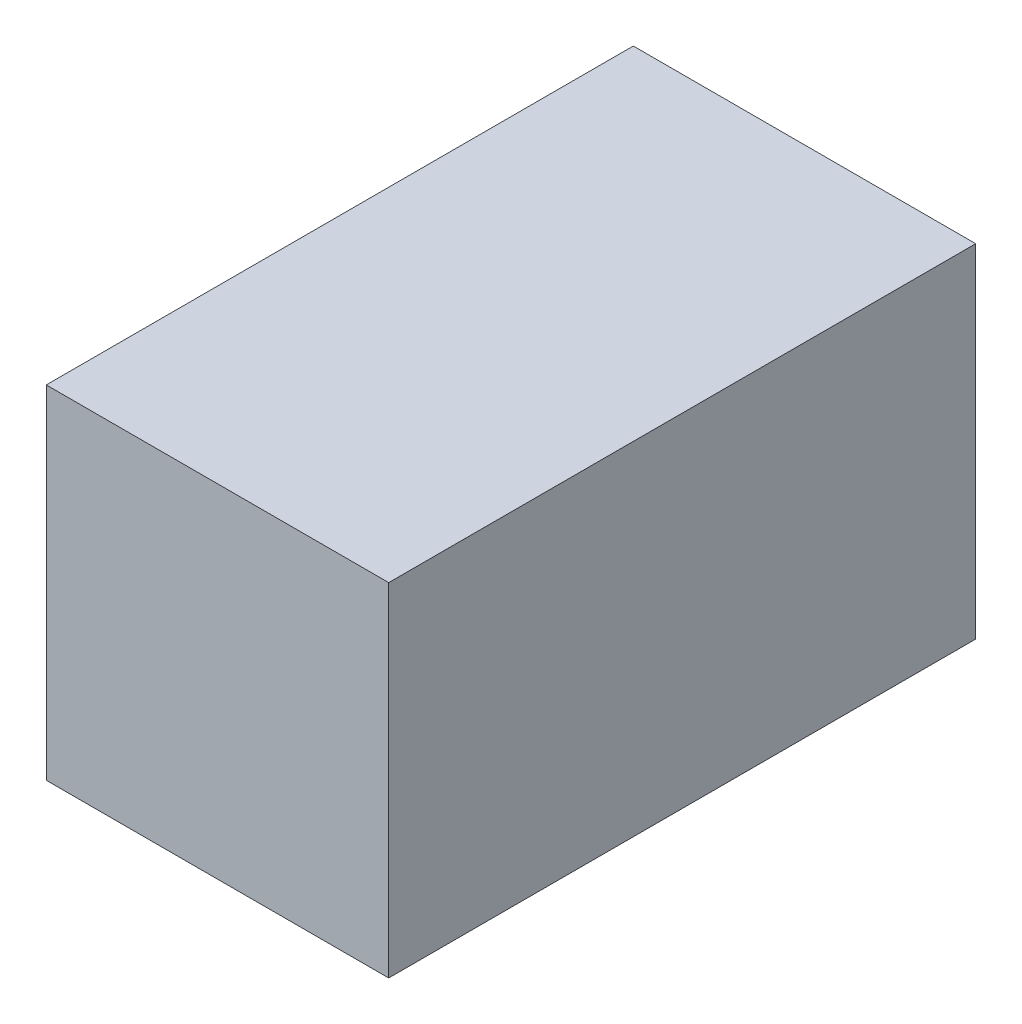
SolidWorks part; units mm, degrees
ref_plane "Front Plane" through (0, 0, 0) normal (0, 0, 1) x (1, 0, 0)
ref_plane "Top Plane" through (0, 0, 0) normal (0, 1, 0) x (1, 0, 0)
ref_plane "Right Plane" through (0, 0, 0) normal (1, 0, 0) x (0, 0, -1)
sketch "Sketch1" plane through (0, 0, 0) normal (0, 0, 1) x (1, 0, 0)
  line L1 (88.9, -88.9) -> (-88.9, -88.9)
  line L2 (88.9, -88.9) -> (88.9, 88.9)
  line L3 (88.9, 88.9) -> (-88.9, 88.9)
  line L4 (-88.9, -88.9) -> (-88.9, 88.9)
  line L5 (88.9, -88.9) -> (-88.9, 88.9) construction
  line L6 (88.9, 88.9) -> (-88.9, -88.9) construction
  point P0 (0, 0)
  dimension "D1" = 177.8
  dimension "D2" = 177.8
extrude "Boss-Extrude1" add sketch "Sketch1" along normal blind 304.8
